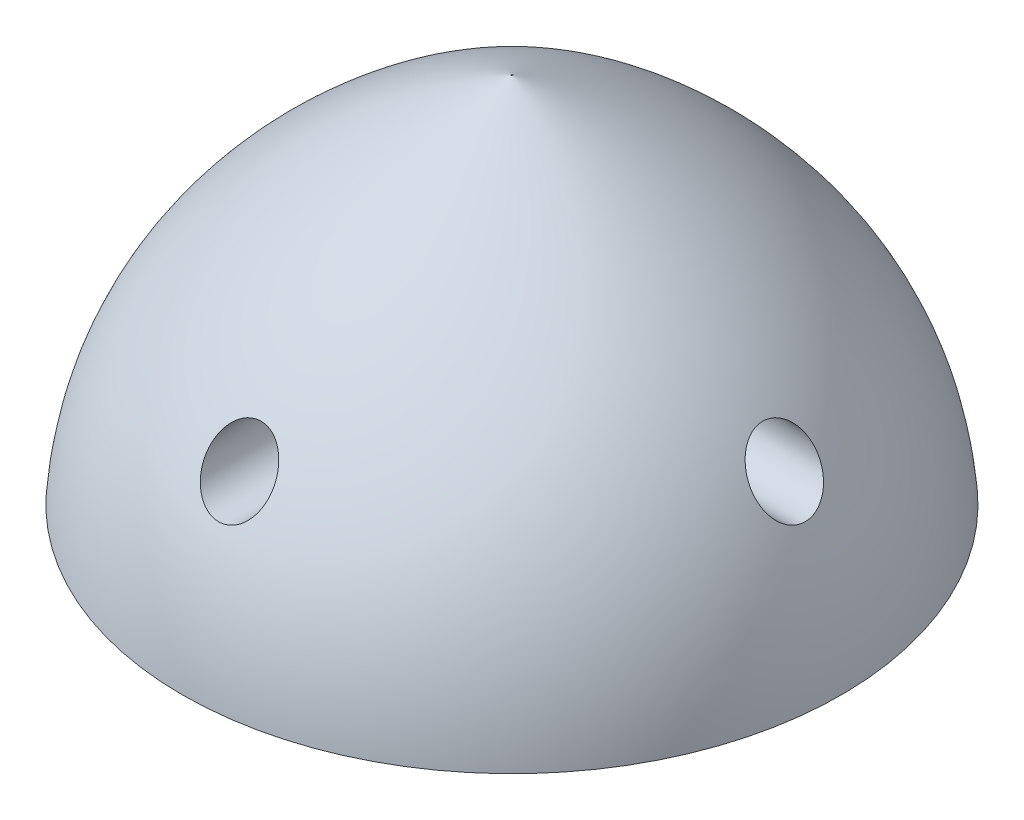
SolidWorks part; units mm, degrees
material "Stainless Steel (ferritic)"
ref_plane "Front Plane" through (0, 0, 0) normal (0, 0, 1) x (1, 0, 0)
ref_plane "Top Plane" through (0, 0, 0) normal (0, 1, 0) x (1, 0, 0)
ref_plane "Right Plane" through (0, 0, 0) normal (1, 0, 0) x (0, 0, -1)
sketch "Sketch1" plane through (0, 0, 0) normal (0, 0, 1) x (1, 0, 0)
  line L0 (0, 52.1873) -> (0, -51.7551) construction
  line L1 (-56.1851, 0) -> (71.7441, 0) construction
  line L2 (0, 0) -> (8000, 0)
  line L3 (0, 0) -> (0, 9000)
  line L4 (0, 9000) -> (13.1109, 9028.6336)
  spline S0 degree 2 poles (13.1109, 9028.6336) (7529.8526, 5849.0531) (8000, 0) knots 0 0 0 0.656149 0.656149 0.656149
  dimension "D1" = 8000
  dimension "D2" = 9000
revolve "Revolve1" add sketch "Sketch1" angle 360 about L0
ref_plane "Plane1" through (0, 0, 8000) normal (0, 0, 1) x (1, 0, 0)
sketch "Sketch2" plane through (0, 0, 8000) normal (0, 0, 1) x (1, 0, 0)
  line L0 (0, 10405.4191) -> (0, -1129.0964) construction
  line L1 (-9821.0503, 0) -> (10254.1125, 0) construction
  circle A0 centre (0, 4000) radius 800
  point P1 (0, 0)
  dimension "D1" = 4000
  dimension "D2" = 1600
extrude "Cut-Extrude1" cut sketch "Sketch2" against normal blind 5333.3333
pattern_circular "CirPattern1" count 4 over 360 about axis through (0, 0, 0) along (0, 1, 0) of "Cut-Extrude1"
